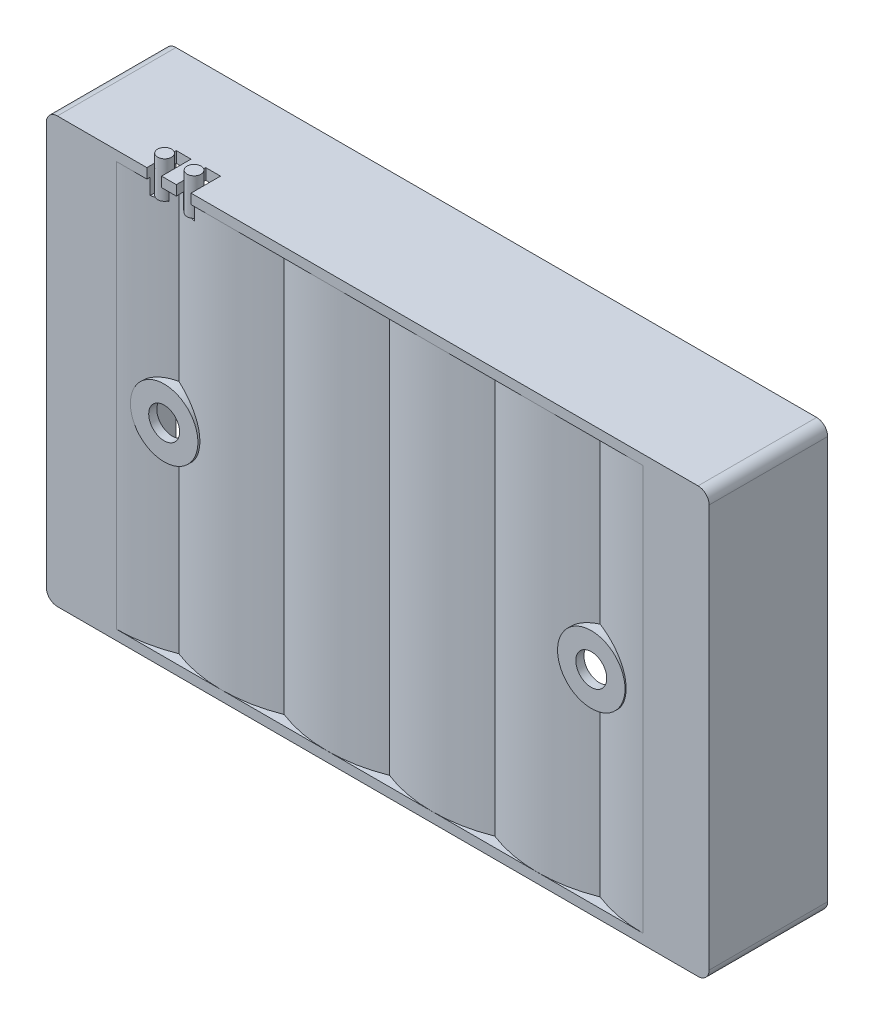
SolidWorks part; units mm, degrees
material "45"
ref_plane "前视基准面" through (0, 0, 0) normal (0, 0, 1) x (1, 0, 0)
ref_plane "上视基准面" through (0, 0, 0) normal (0, 1, 0) x (1, 0, 0)
ref_plane "右视基准面" through (0, 0, 0) normal (1, 0, 0) x (0, 0, -1)
ref_plane "基准面1" through (0, 27.35, 0) normal (0, 1, 0) x (1, 0, 0)
sketch "草图1" plane through (0, 27.35, 0) normal (0, 1, 0) x (1, 0, 0)
  line L0 (28.85, -5.0761) -> (28.85, -6.55)
  line L1 (28.85, -6.55) -> (36, -6.55)
  arc A0 (36, -6.55) -> (28.85, -5.0761) centre (36, 11.5297) cw
extrude "凸台-拉伸1" add sketch "草图1" against normal blind 54.7
ref_plane "基准面2" through (28.85, 0, 0) normal (-1, 0, 0) x (0, -1, 0)
sketch "草图2" plane through (28.85, 0, 0) normal (-1, 0, 0) x (0, -1, 0)
  line L0 (28.85, 6.55) -> (27.35, 6.55)
  line L1 (27.35, 6.55) -> (27.35, 5.0761)
  line L2 (27.35, 5.0761) -> (28.85, 5.0761)
  line L3 (28.85, 5.0761) -> (28.85, 6.55)
extrude "凸台-拉伸2" add sketch "草图2" against normal blind 7.15
sketch "草图3" plane through (28.85, 0, 0) normal (-1, 0, 0) x (0, -1, 0)
  line L0 (-27.35, 6.55) -> (-27.5, 6.55)
  line L1 (-27.5, 6.55) -> (-27.5, 5.0761)
  line L2 (-27.5, 5.0761) -> (-27.35, 5.0761)
  line L3 (-27.35, 5.0761) -> (-27.35, 6.55)
extrude "凸台-拉伸3" add sketch "草图3" against normal blind 7.15
sketch "草图4" plane through (0, 0, 6.55) normal (0, 0, 1) x (1, 0, 0)
  line L0 (28.85, -28.85) -> (28.85, 27.5)
  line L1 (28.85, 27.5) -> (36, 27.5)
  line L2 (36, 27.5) -> (36, -28.85)
  line L3 (36, -28.85) -> (28.85, -28.85)
extrude "凸台-拉伸4" add sketch "草图4" along normal blind 1.5
sketch "草图5" plane through (28.85, 0, 0) normal (-1, 0, 0) x (0, 0, 1)
  line L0 (5.0761, 27.5) -> (8.05, 27.5)
  line L1 (8.05, 27.5) -> (8.05, -28.85)
  line L2 (8.05, -28.85) -> (5.0761, -28.85)
  line L3 (5.0761, -28.85) -> (5.0761, 27.5)
extrude "凸台-拉伸5" add sketch "草图5" along normal blind 14.3
ref_plane "基准面3" through (0, -27.35, 0) normal (0, -1, 0) x (1, 0, 0)
sketch "草图6" plane through (0, -27.35, 0) normal (0, -1, 0) x (1, 0, 0)
  line L0 (14.55, 5.0761) -> (28.85, 5.0761)
  arc A0 (28.85, 5.0761) -> (14.55, 5.0761) centre (21.7, -11.5297) ccw
extrude "切除-拉伸1" cut sketch "草图6" against normal blind 54.7
sketch "草图7" plane through (14.55, 0, 0) normal (-1, 0, 0) x (0, 0, 1)
  line L0 (5.0761, 27.5) -> (8.05, 27.5)
  line L1 (8.05, 27.5) -> (8.05, -28.85)
  line L2 (8.05, -28.85) -> (5.0761, -28.85)
  line L3 (5.0761, -28.85) -> (5.0761, 27.5)
extrude "凸台-拉伸6" add sketch "草图7" along normal blind 14.3
sketch "草图8" plane through (0, -27.35, 0) normal (0, -1, 0) x (1, 0, 0)
  line L0 (0.25, 5.0761) -> (14.55, 5.0761)
  arc A0 (14.55, 5.0761) -> (0.25, 5.0761) centre (7.4, -11.5297) ccw
extrude "切除-拉伸2" cut sketch "草图8" against normal blind 54.7
sketch "草图9" plane through (0.25, 0, 0) normal (-1, 0, 0) x (0, 0, 1)
  line L0 (5.0761, 27.5) -> (8.05, 27.5)
  line L1 (8.05, 27.5) -> (8.05, -28.85)
  line L2 (8.05, -28.85) -> (5.0761, -28.85)
  line L3 (5.0761, -28.85) -> (5.0761, 27.5)
extrude "凸台-拉伸7" add sketch "草图9" along normal blind 14.3
sketch "草图10" plane through (0, -27.35, 0) normal (0, -1, 0) x (1, 0, 0)
  line L0 (-14.05, 5.0761) -> (0.25, 5.0761)
  arc A0 (0.25, 5.0761) -> (-14.05, 5.0761) centre (-6.9, -11.5297) ccw
extrude "切除-拉伸3" cut sketch "草图10" against normal blind 54.7
sketch "草图11" plane through (-14.05, 0, 0) normal (-1, 0, 0) x (0, 0, 1)
  line L0 (5.0761, -28.85) -> (5.0761, 27.5)
  line L1 (5.0761, 27.5) -> (8.05, 27.5)
  line L2 (8.05, 27.5) -> (8.05, -28.85)
  line L3 (8.05, -28.85) -> (5.0761, -28.85)
extrude "凸台-拉伸8" add sketch "草图11" along normal blind 14.3
sketch "草图12" plane through (0, -27.35, 0) normal (0, -1, 0) x (1, 0, 0)
  line L0 (-28.35, 5.0761) -> (-14.05, 5.0761)
  arc A0 (-14.05, 5.0761) -> (-28.35, 5.0761) centre (-21.2, -11.5297) ccw
extrude "切除-拉伸4" cut sketch "草图12" against normal blind 54.7
sketch "草图13" plane through (-28.35, 0, 0) normal (-1, 0, 0) x (0, 0, 1)
  line L0 (5.0761, 27.35) -> (5.0761, 27.5)
  line L1 (5.0761, 27.5) -> (8.05, 27.5)
  line L2 (8.05, 27.5) -> (8.05, -28.85)
  line L3 (8.05, -28.85) -> (5.0761, -28.85)
  line L4 (5.0761, -28.85) -> (5.0761, -27.35)
  spline S0 degree 3 poles (5.0761, -27.35) (5.0761, -9.1167) (5.0761, 9.1167) (5.0761, 27.35) knots 0 0 0 0 1 1 1 1
extrude "凸台-拉伸9" add sketch "草图13" along normal blind 7.15
sketch "草图14" plane through (0, -27.35, 0) normal (0, -1, 0) x (1, 0, 0)
  line L0 (-35.5, 5.0761) -> (-28.35, 5.0761)
  line L1 (-35.5, 6.55) -> (-35.5, 5.0761)
  arc A0 (-28.35, 5.0761) -> (-35.5, 6.55) centre (-35.5, -11.5297) ccw
extrude "切除-拉伸5" cut sketch "草图14" against normal blind 54.7
sketch "草图15" plane through (0, 27.5, 0) normal (0, 1, 0) x (-1, 0, 0)
  line L0 (21.2, 8.05) -> (6.9, 8.05)
  arc A0 (6.9, 8.05) -> (14.05, 6.6978) centre (6.9, -11.5297) cw
  arc A1 (14.05, 6.6978) -> (21.2, 8.05) centre (21.2, -11.5297) cw
extrude "切除-拉伸6" cut sketch "草图15" against normal blind 55
sketch "草图16" plane through (0, 27.5, 0) normal (0, 1, 0) x (-1, 0, 0)
  line L0 (6.9, 8.05) -> (-7.4, 8.05)
  arc A0 (-7.4, 8.05) -> (-0.25, 6.6978) centre (-7.4, -11.5297) cw
  arc A1 (-0.25, 6.6978) -> (6.9, 8.05) centre (6.9, -11.5297) cw
extrude "切除-拉伸7" cut sketch "草图16" against normal blind 55
sketch "草图17" plane through (0, 27.5, 0) normal (0, 1, 0) x (-1, 0, 0)
  line L0 (-7.4, 8.05) -> (-21.7, 8.05)
  arc A0 (-21.7, 8.05) -> (-14.55, 6.6978) centre (-21.7, -11.5297) cw
  arc A1 (-14.55, 6.6978) -> (-7.4, 8.05) centre (-7.4, -11.5297) cw
extrude "切除-拉伸8" cut sketch "草图17" against normal blind 55
sketch "草图18" plane through (0, 27.5, 0) normal (0, 1, 0) x (-1, 0, 0)
  line L0 (-21.7, 8.05) -> (-36, 8.05)
  arc A0 (-36, 8.05) -> (-28.85, 6.6978) centre (-36, -11.5297) cw
  arc A1 (-28.85, 6.6978) -> (-21.7, 8.05) centre (-21.7, -11.5297) cw
extrude "切除-拉伸9" cut sketch "草图18" against normal blind 55
sketch "草图19" plane through (0, 27.5, 0) normal (0, 1, 0) x (-1, 0, 0)
  line L0 (35.5, 8.05) -> (21.2, 8.05)
  arc A0 (21.2, 8.05) -> (28.35, 6.6978) centre (21.2, -11.5297) cw
  arc A1 (28.35, 6.6978) -> (35.5, 8.05) centre (35.5, -11.5297) cw
extrude "切除-拉伸10" cut sketch "草图19" against normal blind 55
sketch "草图20" plane through (0, 0, 5.0761) normal (0, 0, -1) x (-1, 0, 0)
  line L0 (35.5, -28.85) -> (-36, -28.85)
  line L1 (-36, -28.85) -> (-36, -27.35)
  line L2 (-36, -27.35) -> (35.5, -27.35)
  line L3 (35.5, -27.35) -> (35.5, -28.85)
extrude "凸台-拉伸10" add sketch "草图20" along normal blind 13.1261
sketch "草图21" plane through (0, 0, 5.0761) normal (0, 0, -1) x (-1, 0, 0)
  line L0 (35.5, 27.35) -> (-36, 27.35)
  line L1 (-36, 27.35) -> (-36, 27.5)
  line L2 (-36, 27.5) -> (35.5, 27.5)
  line L3 (35.5, 27.5) -> (35.5, 27.35)
extrude "凸台-拉伸11" add sketch "草图21" along normal blind 13.1261
sketch "草图22" plane through (-35.5, 0, 0) normal (-1, 0, 0) x (0, 0, 1)
  line L0 (8.05, 27.5) -> (8.05, -28.85)
  line L1 (8.05, -28.85) -> (-8.05, -28.85)
  line L2 (-8.05, -28.85) -> (-8.05, 27.5)
  line L3 (-8.05, 27.5) -> (8.05, 27.5)
extrude "凸台-拉伸12" add sketch "草图22" along normal blind 9.5
sketch "草图23" plane through (36, 0, 0) normal (1, 0, 0) x (0, 0, -1)
  line L0 (8.05, 27.5) -> (8.05, -28.85)
  line L1 (8.05, -28.85) -> (-8.05, -28.85)
  line L2 (-8.05, -28.85) -> (-8.05, 27.5)
  line L3 (-8.05, 27.5) -> (8.05, 27.5)
extrude "凸台-拉伸13" add sketch "草图23" along normal blind 9
sketch "草图24" plane through (-35.5, 0, 0) normal (1, 0, 0) x (0, 0, -1)
  line L0 (8.05, 27.35) -> (-6.55, 27.35)
  line L1 (-6.55, 27.35) -> (-6.55, -27.35)
  line L2 (-6.55, -27.35) -> (8.05, -27.35)
  line L3 (8.05, -27.35) -> (8.05, 27.35)
extrude "切除-拉伸11" cut sketch "草图24" against normal blind 8
sketch "草图25" plane through (36, 0, 0) normal (-1, 0, 0) x (0, 0, 1)
  line L0 (-8.05, -27.35) -> (6.55, -27.35)
  line L1 (6.55, -27.35) -> (6.55, 27.35)
  line L2 (6.55, 27.35) -> (-8.05, 27.35)
  line L3 (-8.05, 27.35) -> (-8.05, -27.35)
extrude "切除-拉伸12" cut sketch "草图25" against normal blind 7.5
sketch "草图26" plane through (0, 27.5, 0) normal (0, 1, 0) x (-1, 0, 0)
  line L0 (-45, 8.05) -> (45, 8.05)
  line L1 (45, 8.05) -> (45, -8.05)
  line L2 (45, -8.05) -> (-45, -8.05)
  line L3 (-45, -8.05) -> (-45, 8.05)
extrude "凸台-拉伸14" add sketch "草图26" along normal blind 1.35
sketch "草图27" plane through (0, 0, 0) normal (0, 1, 0) x (1, 0, 0)
  line L0 (-33.58, -8.05) -> (-29, -8.05)
  line L1 (-29, -8.05) -> (-29, -6.6978)
  line L2 (-29, -6.6978) -> (-33.58, -6.6978)
  line L3 (-33.58, -6.6978) -> (-33.58, -8.05)
  line L4 (-29, -8.05) -> (-29, -6.6978) construction
revolve "旋转1" add sketch "草图27" angle 360 about L4
sketch "草图28" plane through (0, 0, 0) normal (0, 1, 0) x (1, 0, 0)
  line L0 (29, -8.05) -> (33.58, -8.05)
  line L1 (33.58, -8.05) -> (33.58, -6.6978)
  line L2 (33.58, -6.6978) -> (29, -6.6978)
  line L3 (29, -6.6978) -> (29, -8.05)
  line L4 (29, -6.6978) -> (29, -8.05) construction
revolve "旋转2" add sketch "草图28" angle 360 about L4
ref_plane "基准面4" through (0, 0, 5.0761) normal (0, 0, -1) x (-1, 0, 0)
hole_wizard "M3.5 六角头机械螺钉的柱形沉头孔1" positions "草图30" profile "草图29" counterbore size "M3.5" standard "Ansi Metric"
sketch "草图30" plane through (0, 0, 5.0761) normal (0, 0, -1) x (-1, 0, 0)
  point P0 (-29, 0)
  point P1 (29, 0)
sketch "草图29" plane through (29, 0, 5.0761) normal (1, 0, 0) x (0, 1, 0)
  line L0 (0, 0) -> (0, 2.9739)
  line L1 (0, 2.9739) -> (2.1, 2.9739)
  line L3 (2.1, 2.9739) -> (2.1, 1.8739)
  line L4 (2.1, 1.8739) -> (4, 1.8739)
  line L5 (4, 1.8739) -> (4, 0)
  line L7 (4, 0) -> (0, 0)
  line L11 (0, -6.35) -> (0, 107.95) construction
  dimension "通孔孔直径" = 4.2
  dimension "通孔孔深度" = 2.9739
  dimension "柱形沉头孔直径" = 8
  dimension "柱形沉头孔深度" = 1.8739
fillet "圆角1" radius 1.5 4 edges at (45, 28.85, 0) (-45, 28.85, 0) (-45, -28.85, 0) (45, -28.85, 0)
sketch "草图31" plane through (0, 28.85, 0) normal (0, 1, 0) x (1, 0, 0)
  line L0 (-45, -8.05) -> (-45, 8.05) construction
  line L1 (-43.5, -8.05) -> (43.5, -8.05) construction
  point P0 (-31, -5.05)
  dimension "D1" = 14
  dimension "D2" = 3
sketch "草图32" plane through (0, 28.85, 0) normal (0, 1, 0) x (1, 0, 0)
  line L0 (-43.5, -8.05) -> (43.5, -8.05) construction
  line L1 (-31.35, -8.05) -> (-29.35, -8.05)
  line L2 (-31.35, -8.05) -> (-31.35, -4.05)
  line L3 (-31.35, -4.05) -> (-29.35, -4.05)
  line L4 (-25.35, -8.05) -> (-25.35, -4.05)
  line L5 (-29.35, -4.05) -> (-29.35, -8.05)
  line L6 (-27.35, -4.05) -> (-27.35, -8.05)
  line L7 (-27.35, -4.05) -> (-25.35, -4.05)
  line L8 (-27.35, -8.05) -> (-25.35, -8.05)
  dimension "D1" = 6
  dimension "D2" = 4
  dimension "D3" = 3
  dimension "D4" = 2
  dimension "D5" = 2
extrude "切除-拉伸13" cut sketch "草图32" against normal blind 3.5
sketch "草图35" plane through (0, 25.35, 0) normal (0, 1, 0) x (1, 0, 0)
  line L0 (-29.35, -8.05) -> (-29.35, -4.05) construction
  line L1 (-27.35, -4.05) -> (-27.35, -8.05) construction
  circle A1 centre (-30.35, -6.6418) radius 0.95
  circle A2 centre (-26.35, -6.6418) radius 0.95
  dimension "D1" = 1
  dimension "D2" = 1.9
  dimension "D3" = 1
extrude "凸台-拉伸15" add sketch "草图35" along normal blind 5
